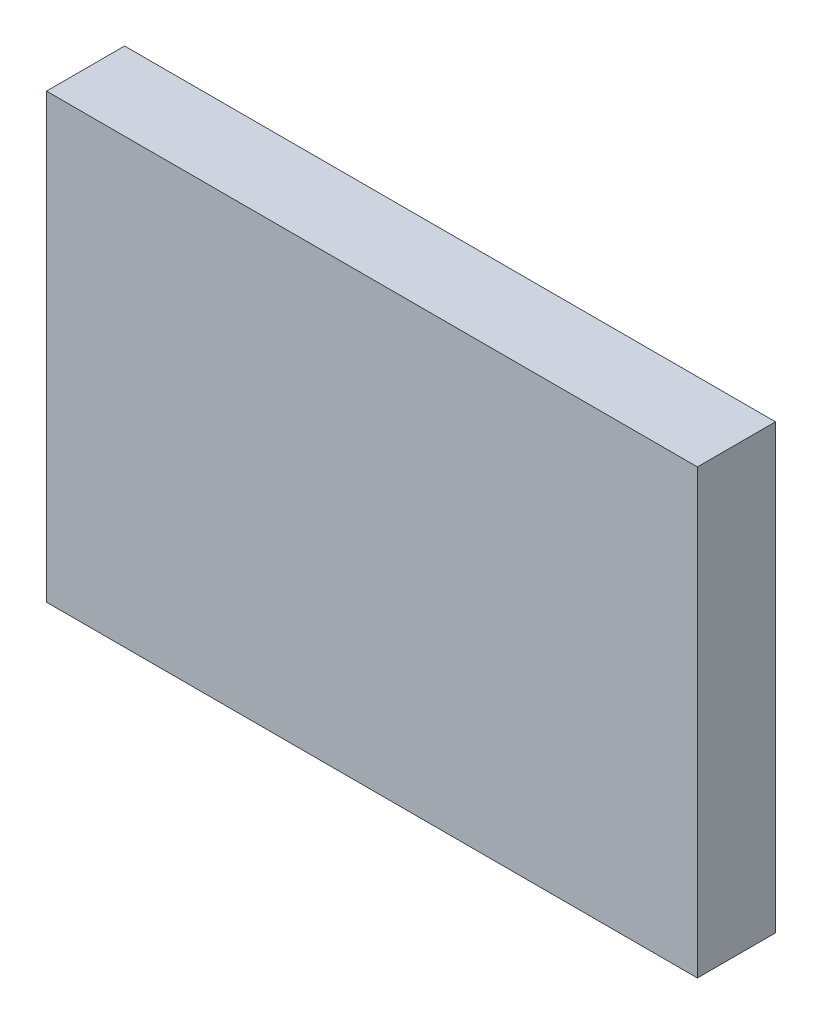
SolidWorks part; units mm, degrees
ref_plane "Plano frontal" through (0, 0, 0) normal (0, 0, 1) x (1, 0, 0)
ref_plane "Plano superior" through (0, 0, 0) normal (0, 1, 0) x (1, 0, 0)
ref_plane "Plano direito" through (0, 0, 0) normal (1, 0, 0) x (0, 0, -1)
sketch "Esboço1" plane through (0, 0, 0) normal (0, 0, 1) x (1, 0, 0)
  line L1 (-62.5, 42.5) -> (62.5, 42.5)
  line L2 (-62.5, 42.5) -> (-62.5, -42.5)
  line L3 (-62.5, -42.5) -> (62.5, -42.5)
  line L4 (62.5, 42.5) -> (62.5, -42.5)
  line L5 (-62.5, 42.5) -> (62.5, -42.5) construction
  line L6 (-62.5, -42.5) -> (62.5, 42.5) construction
  point P0 (0, 0)
  dimension "D1" = 125
  dimension "D2" = 85
extrude "Ressalto-extrusão1" add sketch "Esboço1" along normal blind 15
